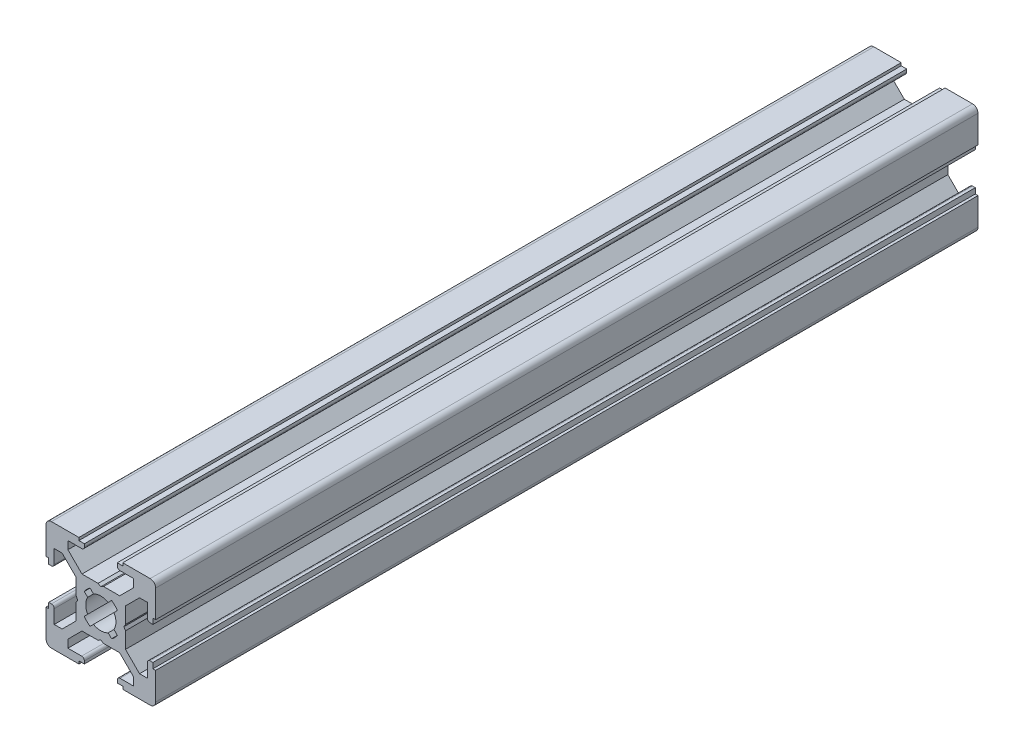
SolidWorks part; units mm, degrees
material "1060 Сплав"
ref_plane "Спереди" through (0, 0, 0) normal (0, 0, 1) x (1, 0, 0)
ref_plane "Сверху" through (0, 0, 0) normal (0, 1, 0) x (1, 0, 0)
ref_plane "Справа" through (0, 0, 0) normal (1, 0, 0) x (0, 0, -1)
sketch "Эскиз1" plane through (0, 0, 0) normal (0, 0, 1) x (1, 0, 0)
  line L0 (0, 10) -> (20, 10) construction
  line L1 (0, 0) -> (20, 0) construction
  line L2 (0, 0) -> (0, 14) construction
  line L3 (1, 20) -> (6, 20)
  line L4 (20, 0) -> (20, 20) construction
  line L5 (10, 0) -> (10, 20) construction
  line L6 (0.5, 13) -> (1, 13)
  line L7 (1.5, 13.5) -> (1.5, 16)
  line L8 (2.9393, 16) -> (5.5, 13.4393)
  line L9 (5.5, 13.4393) -> (5.5, 10.5)
  line L10 (1.5, 16) -> (2.9393, 16)
  line L11 (4, 17.0607) -> (4, 18.5)
  line L12 (0, 20) -> (10, 10) construction
  line L13 (7, 19.5) -> (7, 19)
  line L14 (6.5, 18.5) -> (4, 18.5)
  line L15 (4, 17.0607) -> (6.5607, 14.5)
  line L16 (6.5607, 14.5) -> (9.5, 14.5)
  line L17 (6.9799, 11.9594) -> (7.5988, 11.3405)
  line L18 (8.0406, 13.0201) -> (8.6595, 12.4012)
  line L19 (0.5, 13) -> (0.5, 14)
  line L20 (0.5, 14) -> (0, 14)
  line L21 (7, 19.5) -> (6, 19.5)
  line L22 (6, 19.5) -> (6, 20)
  line L23 (10, 20) -> (20, 20) construction
  line L24 (0, 14) -> (0, 19)
  line L25 (9.5, 14.5) -> (10, 14.2113)
  line L26 (5.5, 10.5) -> (5.7887, 10)
  line L27 (14, 20) -> (19, 20)
  line L28 (20, 20) -> (10, 10) construction
  line L29 (20, 19) -> (20, 14)
  line L30 (19.5, 14) -> (20, 14)
  line L31 (19.5, 13) -> (19.5, 14)
  line L32 (19.5, 13) -> (19, 13)
  line L33 (18.5, 13.5) -> (18.5, 16)
  line L34 (17.0607, 16) -> (18.5, 16)
  line L35 (17.0607, 16) -> (14.5, 13.4393)
  line L36 (14.5, 13.4393) -> (14.5, 10.5)
  line L37 (14.5, 10.5) -> (14.2113, 10)
  line L38 (13.0201, 11.9594) -> (12.4012, 11.3405)
  line L39 (11.9594, 13.0201) -> (11.3405, 12.4012)
  line L40 (13.4393, 14.5) -> (10.5, 14.5)
  line L41 (10.5, 14.5) -> (10, 14.2113)
  line L42 (16, 17.0607) -> (13.4393, 14.5)
  line L43 (16, 18.5) -> (16, 17.0607)
  line L44 (13.5, 18.5) -> (16, 18.5)
  line L45 (13, 19.5) -> (13, 19)
  line L46 (13, 19.5) -> (14, 19.5)
  line L47 (14, 19.5) -> (14, 20)
  line L48 (20, 6) -> (20, 1)
  line L49 (20, 0) -> (10, 10) construction
  line L50 (19, 0) -> (14, 0)
  line L51 (14, 0.5) -> (14, 0)
  line L52 (13, 0.5) -> (14, 0.5)
  line L53 (13, 0.5) -> (13, 1)
  line L54 (13.5, 1.5) -> (16, 1.5)
  line L55 (16, 2.9393) -> (16, 1.5)
  line L56 (16, 2.9393) -> (13.4393, 5.5)
  line L57 (13.4393, 5.5) -> (10.5, 5.5)
  line L58 (10.5, 5.5) -> (10, 5.7887)
  line L59 (11.9594, 6.9799) -> (11.3405, 7.5988)
  line L60 (13.0201, 8.0406) -> (12.4012, 8.6595)
  line L61 (14.5, 6.5607) -> (14.5, 9.5)
  line L62 (14.5, 9.5) -> (14.2113, 10)
  line L63 (17.0607, 4) -> (14.5, 6.5607)
  line L64 (18.5, 4) -> (17.0607, 4)
  line L65 (18.5, 6.5) -> (18.5, 4)
  line L66 (19.5, 7) -> (19, 7)
  line L67 (19.5, 7) -> (19.5, 6)
  line L68 (19.5, 6) -> (20, 6)
  line L69 (6, 0) -> (1, 0)
  line L70 (0, 0) -> (10, 10) construction
  line L71 (0, 1) -> (0, 6)
  line L72 (0.5, 6) -> (0, 6)
  line L73 (0.5, 7) -> (0.5, 6)
  line L74 (0.5, 7) -> (1, 7)
  line L75 (1.5, 6.5) -> (1.5, 4)
  line L76 (2.9393, 4) -> (1.5, 4)
  line L77 (2.9393, 4) -> (5.5, 6.5607)
  line L78 (5.5, 6.5607) -> (5.5, 9.5)
  line L79 (5.5, 9.5) -> (5.7887, 10)
  line L80 (6.9799, 8.0406) -> (7.5988, 8.6595)
  line L81 (8.0406, 6.9799) -> (8.6595, 7.5988)
  line L82 (6.5607, 5.5) -> (9.5, 5.5)
  line L83 (9.5, 5.5) -> (10, 5.7887)
  line L84 (4, 2.9393) -> (6.5607, 5.5)
  line L85 (4, 1.5) -> (4, 2.9393)
  line L86 (6.5, 1.5) -> (4, 1.5)
  line L87 (7, 0.5) -> (7, 1)
  line L88 (7, 0.5) -> (6, 0.5)
  line L89 (6, 0.5) -> (6, 0)
  arc A0 (7.5988, 11.3405) -> (7.25, 10) centre (10, 10) ccw
  arc A1 (10, 12.75) -> (8.6595, 12.4012) centre (10, 10) ccw
  arc A2 (8.0406, 13.0201) -> (6.9799, 11.9594) centre (10, 10) ccw
  arc A3 (7, 19) -> (6.5, 18.5) centre (6.5, 19) cw
  arc A4 (1, 13) -> (1.5, 13.5) centre (1, 13.5) ccw
  arc A5 (0, 19) -> (1, 20) centre (1, 19) cw
  arc A6 (19, 20) -> (20, 19) centre (19, 19) cw
  arc A7 (19, 13) -> (18.5, 13.5) centre (19, 13.5) cw
  arc A8 (13.0201, 11.9594) -> (11.9594, 13.0201) centre (10, 10) ccw
  arc A9 (12.75, 10) -> (12.4012, 11.3405) centre (10, 10) ccw
  arc A10 (11.3405, 12.4012) -> (10, 12.75) centre (10, 10) ccw
  arc A11 (13, 19) -> (13.5, 18.5) centre (13.5, 19) ccw
  arc A12 (20, 1) -> (19, 0) centre (19, 1) cw
  arc A13 (13, 1) -> (13.5, 1.5) centre (13.5, 1) cw
  arc A14 (11.9594, 6.9799) -> (13.0201, 8.0406) centre (10, 10) ccw
  arc A15 (10, 7.25) -> (11.3405, 7.5988) centre (10, 10) ccw
  arc A16 (12.4012, 8.6595) -> (12.75, 10) centre (10, 10) ccw
  arc A17 (19, 7) -> (18.5, 6.5) centre (19, 6.5) ccw
  arc A18 (1, 0) -> (0, 1) centre (1, 1) cw
  arc A19 (1, 7) -> (1.5, 6.5) centre (1, 6.5) cw
  arc A20 (6.9799, 8.0406) -> (8.0406, 6.9799) centre (10, 10) ccw
  arc A21 (7.25, 10) -> (7.5988, 8.6595) centre (10, 10) ccw
  arc A22 (8.6595, 7.5988) -> (10, 7.25) centre (10, 10) ccw
  arc A23 (7, 1) -> (6.5, 1.5) centre (6.5, 1) ccw
  dimension "D4" = 5.5
  dimension "D13" = 3.6
  dimension "D18" = 0.5
  dimension "D23" = 1
  dimension "D1" = 20
  dimension "D2" = 20
  dimension "D3" = 6
  dimension "D5" = 12
  dimension "D6" = 12
  dimension "D7" = 4
  dimension "D8" = 1.5
  dimension "D9" = 1.5
  dimension "D10" = 4
  dimension "D11" = 1.5
  dimension "D12" = 6
  dimension "D14" = 0.5
  dimension "D15" = 1
  dimension "D16" = 1
  dimension "D17" = 0.5
  dimension "D19" = 30
  dimension "D20" = 0.5
  dimension "D21" = 30
  dimension "D22" = 0.5
  dimension "D24" = 4
extrude "Бобышка-Вытянуть1" add sketch "Эскиз1" along normal blind 150 contours L87 A23 L86 L85 L84 L82 L83 L58 L57 L56 L55 L54 A13 L53 L52 L51 L50 A12 L48 L68 L67 L66 A17 L65 L64 L63 L61 L62 L37 L36 L35 L34 L33 A7 L32 L31 L30 L29 A6 L27 L47 L46 L45 A11 L44 L43 L42 L40 L41 L25 L16
